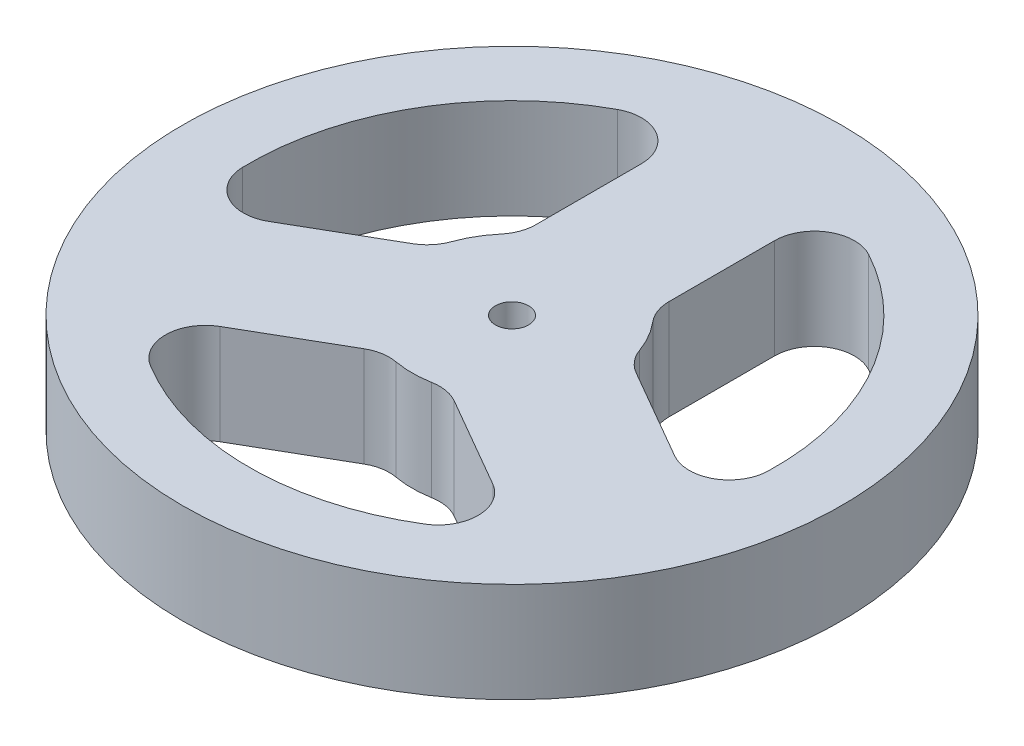
SolidWorks part; units mm, degrees
ref_plane "Płaszczyzna przednia" through (0, 0, 0) normal (0, 0, 1) x (1, 0, 0)
ref_plane "Płaszczyzna górna" through (0, 0, 0) normal (0, 1, 0) x (1, 0, 0)
ref_plane "Płaszczyzna prawa" through (0, 0, 0) normal (1, 0, 0) x (0, 0, -1)
sketch "Szkic1" plane through (0, 0, 0) normal (0, 1, 0) x (1, 0, 0)
  line L0 (0, 15) -> (0, 39.5) construction
  line L1 (-10, 38.2132) -> (-10, 11.1803)
  line L2 (10, 38.2132) -> (10, 11.1803)
  line L3 (28.0936, -27.7669) -> (4.6825, -14.2504)
  line L4 (38.0936, -10.4464) -> (14.6825, 3.0701)
  line L5 (-38.0936, -10.4464) -> (-14.6825, 3.0701)
  line L6 (-28.0936, -27.7669) -> (-4.6825, -14.2504)
  circle A0 centre (0, 0) radius 49.5
  circle A1 centre (0, 0) radius 15
  circle A2 centre (0, 0) radius 2.5
  circle A3 centre (0, 0) radius 39.5
  point P22 (0, 0)
  dimension "D1" = 99
  dimension "D2" = 30
  dimension "D3" = 5
  dimension "D4" = 10
  dimension "D5" = 10
  dimension "D6" = 10
  dimension "D7" = 3
extrude "Dodanie-wyciągnięcie1" add sketch "Szkic1" along normal blind 15 contours A0 A3 | A1 L0 A3 L1 | L0 A1 L2 A3 | L3 A3 L4 A1 | A1 A2 | L5 A3 L6 A1
fillet "Zaokrąglenie1" radius 6 12 edges at (4.6825, 7.5, 14.2504) (14.6825, 7.5, -3.0701) (38.0936, 7.5, 10.4464) (28.0936, 7.5, 27.7669) (-4.6825, 7.5, 14.2504) (10, 7.5, -11.1803) (-10, 7.5, -11.1803) (-14.6825, 7.5, -3.0701) (-28.0936, 7.5, 27.7669) (-38.0936, 7.5, 10.4464) (10, 7.5, -38.2132) (-10, 7.5, -38.2132)
